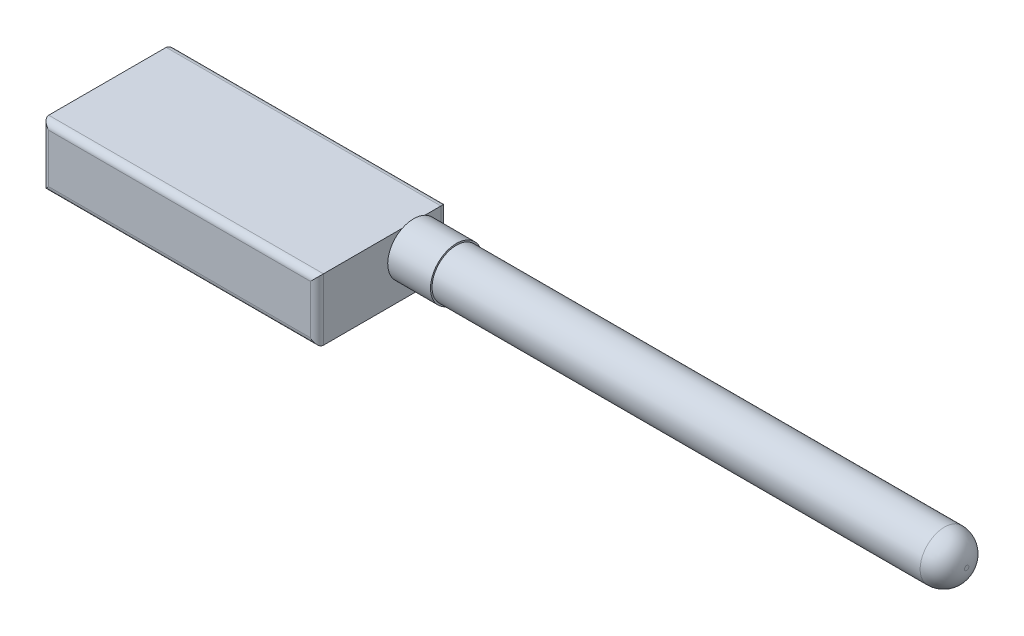
SolidWorks part; units mm, degrees
ref_plane "Front Plane" through (0, 0, 0) normal (0, 0, 1) x (1, 0, 0)
ref_plane "Top Plane" through (0, 0, 0) normal (0, 1, 0) x (1, 0, 0)
ref_plane "Right Plane" through (0, 0, 0) normal (1, 0, 0) x (0, 0, -1)
sketch "Sketch1" plane through (0, 0, 0) normal (0, 1, 0) x (1, 0, 0)
  line L1 (-26.1041, 14.7291) -> (27.4159, 14.7291)
  line L2 (-26.1041, 14.7291) -> (-26.1041, -10.6909)
  line L3 (-26.1041, -10.6909) -> (27.4159, -10.6909)
  line L4 (27.4159, 14.7291) -> (27.4159, -10.6909)
  dimension "D1" = 53.52
  dimension "D2" = 25.42
extrude "Boss-Extrude2" add sketch "Sketch1" along normal blind 12.06 contours L1 L4 L3 L2
sketch "Sketch2" plane through (27.4159, 0, 0) normal (1, 0, 0) x (0, 0, -1)
  line L0 (14.7291, 0) -> (-10.6909, 0) construction
  line L1 (-10.6909, 12.06) -> (-10.6909, 0) construction
  circle A0 centre (8.1513, 7.5138) radius 5.05
  dimension "D1" = 10.1
  dimension "D2" = 7.5138
  dimension "D3" = 18.8422
extrude "Boss-Extrude3" add sketch "Sketch2" along normal blind 8.33
sketch "Sketch3" plane through (35.7459, 0, 0) normal (1, 0, 0) x (0, 0, -1)
  circle A0 centre (8.1513, 7.5138) radius 4.745
  arc A1 (5.9526, 12.06) -> (10.3501, 12.06) centre (8.1513, 7.5138) ccw construction
extrude "Boss-Extrude4" add sketch "Sketch3" along normal blind 12 contours A0
sketch "Sketch4" plane through (47.7459, 0, 0) normal (1, 0, 0) x (0, 0, -1)
  circle A0 centre (8.1513, 7.5138) radius 4.745
extrude "Boss-Extrude5" add sketch "Sketch4" along normal blind 87.4
fillet "Fillet1" radius 4.318 1 edges at (135.1459, 7.5138, -12.8963)
fillet "Fillet2" radius 1.27 4 edges at (-26.1041, 6.03, 10.6909) (0.6559, 12.06, 10.6909) (27.4159, 6.03, 10.6909) (0.6559, 0, 10.6909)
fillet "Fillet3" radius 1.27 4 edges at (27.4159, 6.03, -14.7291) (0.6559, 12.06, -14.7291) (-26.1041, 6.03, -14.7291) (0.6559, 0, -14.7291)
